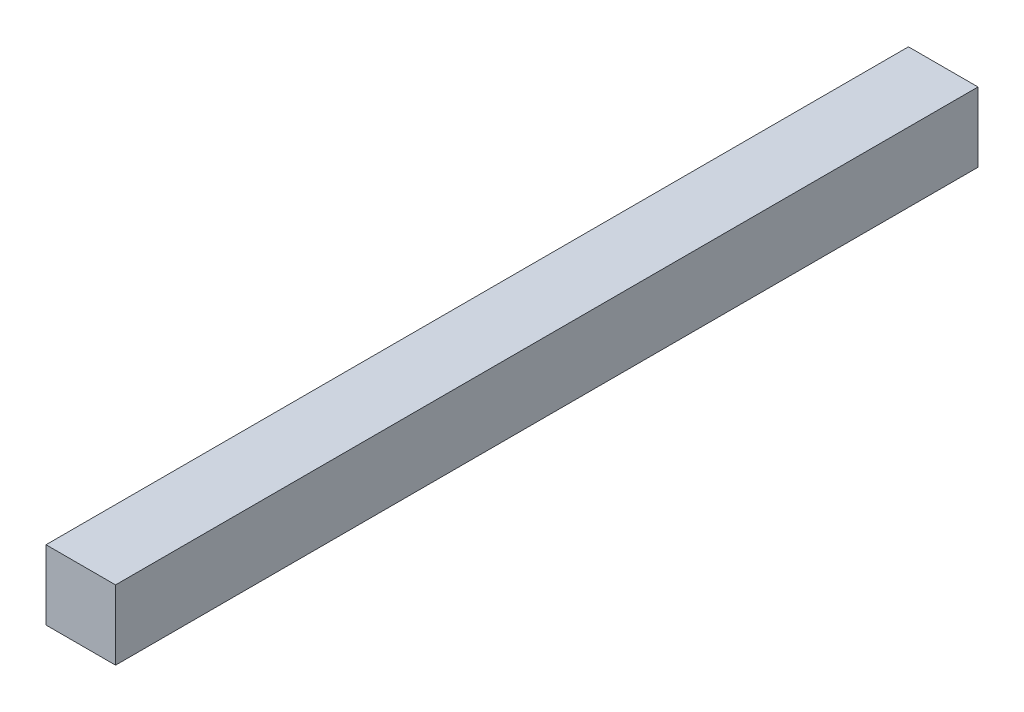
SolidWorks part; units mm, degrees
ref_plane "Płaszczyzna przednia" through (0, 0, 0) normal (0, 0, 1) x (1, 0, 0)
ref_plane "Płaszczyzna górna" through (0, 0, 0) normal (0, 1, 0) x (1, 0, 0)
ref_plane "Płaszczyzna prawa" through (0, 0, 0) normal (1, 0, 0) x (0, 0, -1)
sketch "Szkic1" plane through (0, 0, 0) normal (0, 0, 1) x (1, 0, 0)
  line L1 (-11.4888, 4.2896) -> (-6.4888, 4.2896)
  line L2 (-11.4888, 4.2896) -> (-11.4888, -0.7104)
  line L3 (-11.4888, -0.7104) -> (-6.4888, -0.7104)
  line L4 (-6.4888, 4.2896) -> (-6.4888, -0.7104)
  dimension "D1" = 5
  dimension "D2" = 5
extrude "Dodanie-wyciągnięcie1" add sketch "Szkic1" along normal blind 62
